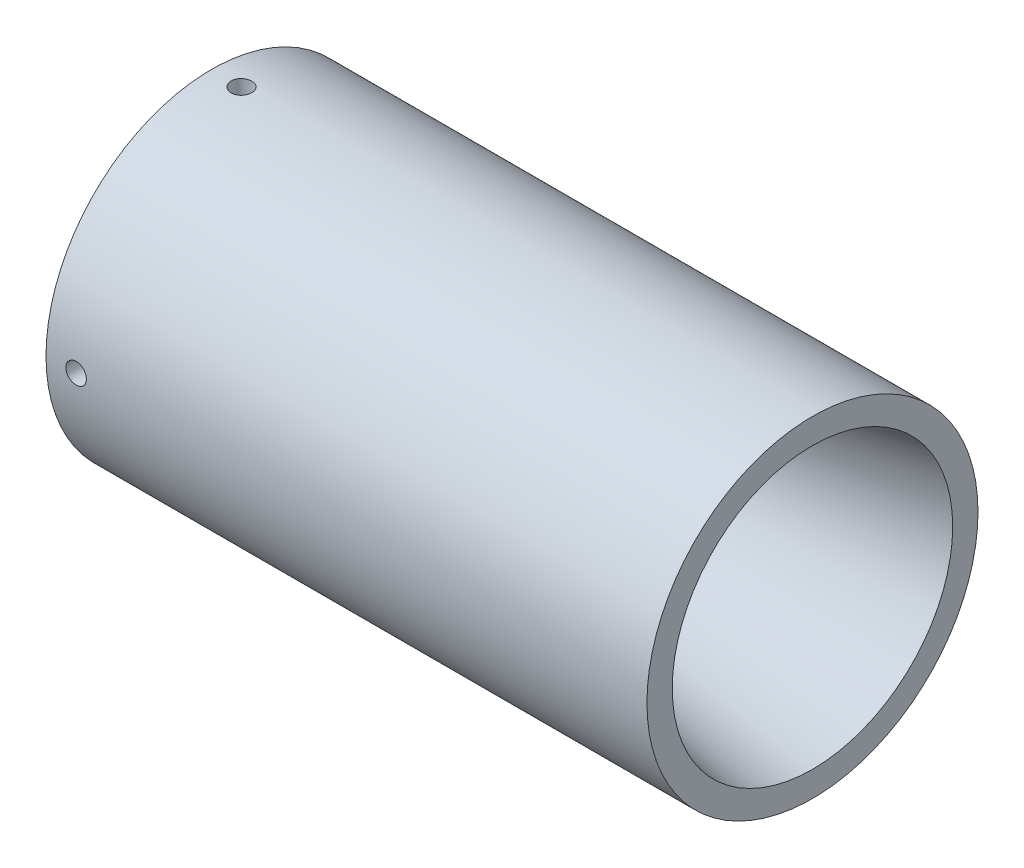
SolidWorks part; units mm, degrees
material "6061-T6 (SS)"
ref_plane "Front Plane" through (0, 0, 0) normal (0, 0, 1) x (1, 0, 0)
ref_plane "Top Plane" through (0, 0, 0) normal (0, 1, 0) x (1, 0, 0)
ref_plane "Right Plane" through (0, 0, 0) normal (1, 0, 0) x (0, 0, -1)
sketch "Sketch1" plane through (0, 0, 0) normal (0, 0, 1) x (1, 0, 0)
  line L0 (-21.9266, 0) -> (26.2178, 0) construction
  line L1 (0, 0) -> (0, 7.5) construction
  line L2 (-233.806, 191.2996) -> (-233.806, 679.2996) construction
  line L3 (0, 7.5) -> (36.5196, 14)
  line L4 (36.5196, 14) -> (36.5196, 16.5263)
  line L5 (36.5196, 16.5263) -> (-23.4804, 16.5263)
  line L6 (-23.4804, 16.5263) -> (-23.4804, 12.5263)
  line L7 (-23.4804, 12.5263) -> (0, 7.5)
  dimension "D1" = 7.5
  dimension "D2" = 14
  dimension "D3" = 2.5263
  dimension "D4" = 4
  dimension "D5" = 12.5263
  dimension "D6" = 60
revolve "Revolve1" add sketch "Sketch1" angle 360 about L0
sketch "Sketch3" plane through (0, 0, 0) normal (0, 1, 0) x (1, 0, 0)
  line L0 (-23.4804, 16.5263) -> (-23.4804, -16.5263) construction
  point P0 (-19.9804, 0)
  dimension "D1" = 3.5
hole_wizard "M2.5 Tapped Hole1" positions "3DSketch1" profile "Sketch4" tap size "M2.5" standard "ISO" end condition through all
sketch3d "3DSketch1"
  point P0 (-20.4804, 0, -16.5263)
  point P2 (-20.4804, 16.5263, 0)
  point P4 (-20.4804, 0, -16.5263)
  dimension "D1" = 3
  dimension "D2" = 3
sketch "Sketch4" plane through (-20.4804, 0, -16.5263) normal (1, 0, 0) x (0, 1, 0)
  line L0 (0, 0) -> (0, 33.0527)
  line L1 (0, 33.0527) -> (1.025, 33.0527)
  line L2 (1.025, 33.0527) -> (1.025, 0)
  line L5 (1.025, 0) -> (0, 0)
  line L11 (0, -6.35) -> (0, 107.95) construction
  dimension "Thru Tap Drill Dia." = 2.05
  dimension "Thru Tap Drill Depth" = 33.0527
cosmetic thread "Hole Thread2"
cosmetic thread "Hole Thread3"
